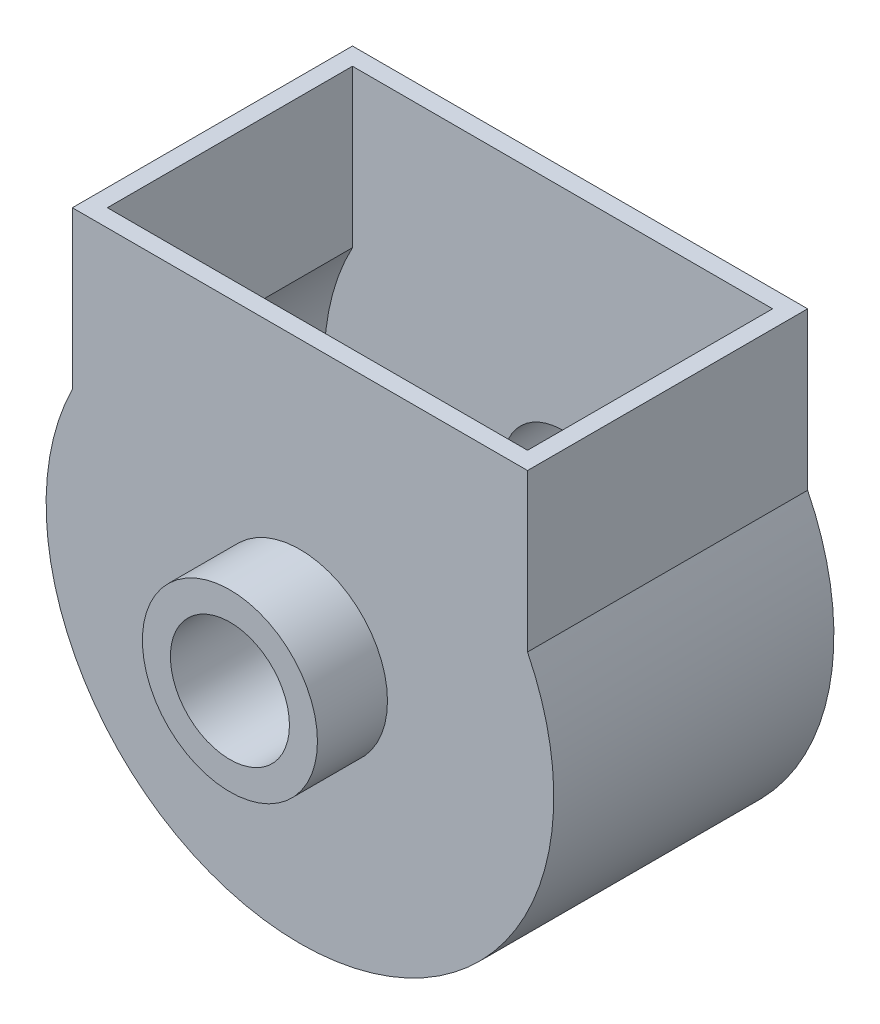
SolidWorks part; units mm, degrees
ref_plane "Front Plane" through (0, 0, 0) normal (0, 0, 1) x (1, 0, 0)
ref_plane "Top Plane" through (0, 0, 0) normal (0, 1, 0) x (1, 0, 0)
ref_plane "Right Plane" through (0, 0, 0) normal (1, 0, 0) x (0, 0, -1)
sketch "Sketch1" plane through (0, 0, 0) normal (0, 0, 1) x (1, 0, 0)
  line L0 (0, 25) -> (0, 17)
  line L1 (0, -17) -> (0, -25)
  arc A0 (0, 25) -> (0, -25) centre (0, 0) ccw
  arc A1 (0, 17) -> (0, -17) centre (0, 0) ccw
  dimension "D1" = 50
  dimension "D2" = 34
extrude "Boss-Extrude1" add sketch "Sketch1" along normal blind 20 and the other way blind 5
sketch "Sketch2" plane through (0, 0, 0) normal (0, 0, 1) x (1, 0, 0)
  line L0 (0, -25) -> (0, -72.5)
  line L1 (0, 25) -> (0, 77)
  line L2 (0, 77) -> (-65, 77)
  line L3 (-65, 77) -> (-65, 32.1131)
  line L6 (0, 17) -> (0, 25)
  line L7 (0, -25) -> (0, -17)
  line L8 (0, 17) -> (0, 25)
  line L9 (0, -25) -> (0, -17)
  arc A0 (-65, 32.1131) -> (0, -72.5) centre (0, 0) ccw
  arc A3 (0, 17) -> (0, -17) centre (0, 0) ccw
  arc A4 (0, 25) -> (0, -25) centre (0, 0) ccw
  arc A5 (0, 17) -> (0, -17) centre (0, 0) ccw
  dimension "D1" = 145
  dimension "D2" = 52
  dimension "D3" = 65
  dimension "D4" = 0
extrude "Boss-Extrude2" add sketch "Sketch2" against normal blind 5
ref_plane "Plane2" through (0, 0, -40) normal (0, 0, 1) x (1, 0, 0)
mirror "Mirror8" about plane through (0, 0, -40) normal (0, 0, 1) of bodies 102
sketch "Sketch3" plane through (0, 0, -75) normal (0, 0, 1) x (1, 0, 0)
  line L0 (-65, 32.1131) -> (-65, 77)
  line L1 (-65, 77) -> (-60, 77)
  line L2 (0, 77) -> (-65, 77) construction
  line L3 (-60, 77) -> (-60, 32.1131)
  line L4 (0, -68.0533) -> (0, -72.5)
  arc A1 (-60, 32.1131) -> (0, -68.0533) centre (0, 0) ccw
  arc A7 (-65, 32.1131) -> (0, -72.5) centre (0, 0) ccw
extrude "Boss-Extrude3" add sketch "Sketch3" along normal up to surface (70 mm away) up to face at (-29.3468, 15.924, -5)
mirror "Mirror9" about plane through (0, 0, 0) normal (1, 0, 0) of bodies 109
